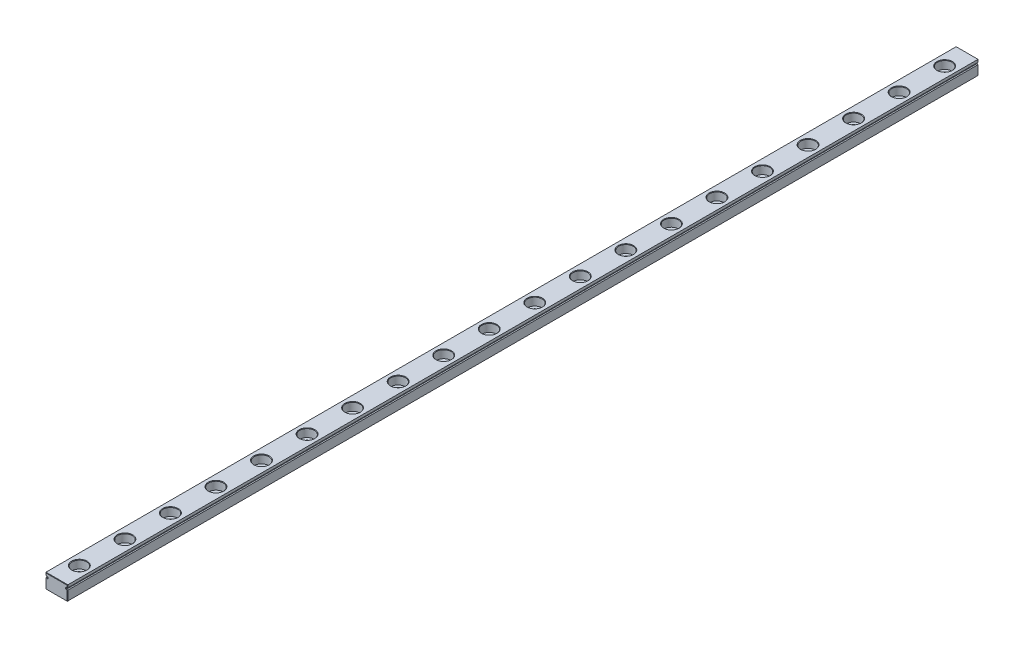
SolidWorks part; units mm, degrees
ref_plane "Front Plane" through (0, 0, 0) normal (0, 0, 1) x (1, 0, 0)
ref_plane "Top Plane" through (0, 0, 0) normal (0, 1, 0) x (1, 0, 0)
ref_plane "Right Plane" through (0, 0, 0) normal (1, 0, 0) x (0, 0, -1)
sketch "Sketch1" plane through (0, 0, 0) normal (0, 0, 1) x (1, 0, 0)
  line L0 (12.2152, 8.9783) -> (12.2152, 7.5373)
  line L1 (11.7152, 7.2283) -> (11.2152, 7.2283)
  line L2 (11.2152, 7.2283) -> (11.2152, 6.7283)
  line L3 (11.2152, 6.7283) -> (11.7152, 6.7283)
  line L4 (12.2152, 6.4192) -> (12.2152, 1.2783)
  line L5 (12.2152, 1.2783) -> (11.9152, 0.9783)
  line L6 (11.9152, 0.9783) -> (0.5152, 0.9783)
  line L7 (0.5152, 0.9783) -> (0.2152, 1.2783)
  line L8 (0.2152, 1.2783) -> (0.2152, 6.4192)
  line L9 (0.7152, 6.7283) -> (1.2152, 6.7283)
  line L10 (1.2152, 6.7283) -> (1.2152, 7.2283)
  line L11 (1.2152, 7.2283) -> (0.7152, 7.2283)
  line L12 (0.2152, 7.5373) -> (0.2152, 8.9783)
  line L13 (0.2152, 8.9783) -> (12.2152, 8.9783)
  arc A0 (12.2152, 7.5373) -> (11.7152, 7.2283) centre (12.2152, 6.9783) ccw
  arc A1 (11.7152, 6.7283) -> (12.2152, 6.4192) centre (12.2152, 6.9783) ccw
  arc A2 (0.2152, 6.4192) -> (0.7152, 6.7283) centre (0.2152, 6.9783) ccw
  arc A3 (0.7152, 7.2283) -> (0.2152, 7.5373) centre (0.2152, 6.9783) ccw
  dimension "D1" = 8
  dimension "D2" = 12
extrude "Boss-Extrude1" add sketch "Sketch1" against normal blind 500
chamfer "Chamfer1" distance 0.2 angle 45 36 edges at (0.2152, 8.2578, 0) (0.5091, 7.4538, 0) (0.9652, 7.2283, 0) (1.2152, 6.9783, 0) (0.9652, 6.7283, 0) (0.5091, 6.5027, 0) (0.2152, 3.8488, 0) (0.3652, 1.1283, 0) (6.2152, 0.9783, 0) (12.0652, 1.1283, 0) (12.2152, 3.8488, 0) (11.9213, 6.5027, 0) (11.4652, 6.7283, 0) (11.2152, 6.9783, 0) (11.4652, 7.2283, 0) (11.9213, 7.4538, 0) (12.2152, 8.2578, 0) (6.2152, 8.9783, 0) (11.9213, 6.5027, -500) (11.4652, 6.7283, -500) (11.2152, 6.9783, -500) (11.4652, 7.2283, -500) (11.9213, 7.4538, -500) (12.2152, 8.2578, -500) (12.2152, 3.8488, -500) (12.0652, 1.1283, -500) (6.2152, 0.9783, -500) (0.3652, 1.1283, -500) (0.2152, 3.8488, -500) (0.5091, 6.5027, -500) (0.9652, 6.7283, -500) (1.2152, 6.9783, -500) (0.9652, 7.2283, -500) (0.5091, 7.4538, -500) (0.2152, 8.2578, -500) (6.2152, 8.9783, -500)
hole_wizard "CBORE for M4 Hex Head Machine Screw1" positions "Sketch2" profile "Sketch3" counterbore size "M4" standard "ANSI Metric" end condition through all
sketch "Sketch2" plane through (0, 8.9783, 0) normal (0, 1, 0) x (1, 0, 0)
  line L0 (6.2152, 0) -> (6.2152, 500) construction
  line L1 (12.0152, 0) -> (0.4152, 0) construction
  line L2 (0.4152, 500) -> (12.0152, 500) construction
  point P0 (6.2152, 12.5)
  dimension "D1" = 12.5
sketch "Sketch3" plane through (6.2152, 8.9783, -12.5) normal (1, 0, 0) x (0, 0, 1)
  line L0 (0, 0) -> (0, 8)
  line L1 (0, 8) -> (2.25, 8)
  line L3 (2.25, 8) -> (2.25, 4.5)
  line L4 (4, 4.5) -> (2.25, 4.5)
  line L5 (4, 4.5) -> (4, 0.25)
  line L6 (4, 0.25) -> (4.25, 0)
  line L7 (4.25, 0) -> (0, 0)
  line L8 (-4, 0.25) -> (-4.25, 0) construction
  line L11 (0, -6.35) -> (0, 107.95) construction
  dimension "Thru Hole Dia." = 4.5
  dimension "Thru Hole Depth" = 8
  dimension "C'Bore Dia." = 8
  dimension "C'Bore Depth" = 4.5
  dimension "Near C'Sink Dia." = 8.5
  dimension "Near C'Sink Angle" = 90
pattern_linear "LPattern1" count 20 spacing 25 along (0, 0, -1) of "CBORE for M4 Hex Head Machine Screw1"
